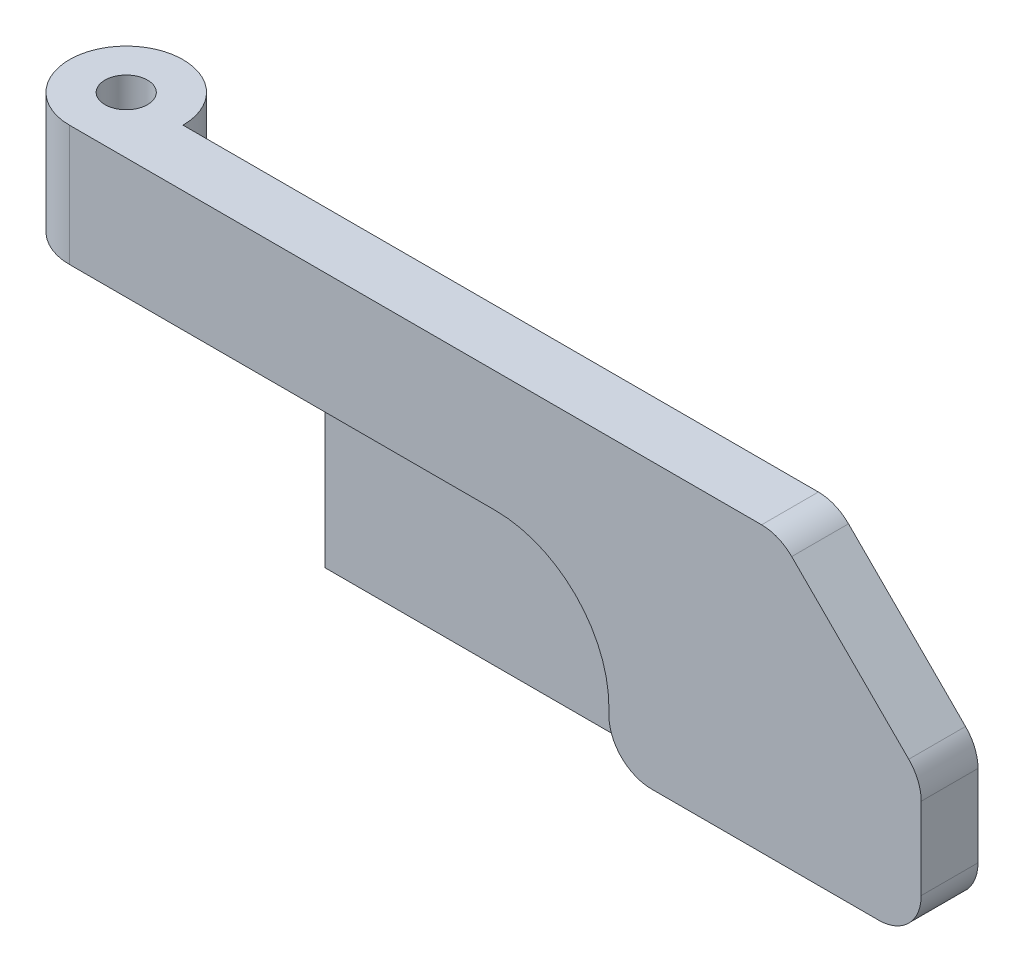
SolidWorks part; units mm, degrees
ref_plane "Alzado" through (0, 0, 0) normal (0, 0, 1) x (1, 0, 0)
ref_plane "Planta" through (0, 0, 0) normal (0, 1, 0) x (1, 0, 0)
ref_plane "Vista lateral" through (0, 0, 0) normal (1, 0, 0) x (0, 0, -1)
sketch "Croquis1" plane through (0, 0, 0) normal (0, 1, 0) x (1, 0, 0)
  line L0 (4, 0) -> (60, 0)
  line L1 (0, -4) -> (60, -4)
  line L2 (60, -4) -> (60, 0)
  circle A0 centre (0, 0) radius 1.5
  circle A1 centre (0, 0) radius 4
  dimension "D1" = 3
  dimension "D2" = 8
  dimension "D3" = 60
extrude "Saliente-Extruir1" add sketch "Croquis1" along normal blind 20 contours A1 A0 | A1 L1 L2 L0
sketch "Croquis2" plane through (0, 0, 4) normal (0, 0, 1) x (1, 0, 0)
  line L0 (16, 11.5) -> (16, 0)
  line L1 (0, 0) -> (60, 0) construction
  line L2 (16, 0) -> (-11.8072, 0)
  line L3 (-11.8072, 0) -> (-11.8072, 11.5)
  line L4 (-11.8072, 11.5) -> (16, 11.5)
  line L5 (-4, 20) -> (-4, 0) construction
  dimension "D1" = 11.5
  dimension "D2" = 20
extrude "Cortar-Extruir1" cut sketch "Croquis2" against normal blind 20
sketch "Croquis3" plane through (0, 0, 4) normal (0, 0, 1) x (1, 0, 0)
  line L0 (16, 0) -> (16, 11.5)
  line L1 (16, 11.5) -> (38, 11.5)
  line L2 (38, 11.5) -> (38, 0)
  line L3 (16, 0) -> (60, 0) construction
  line L4 (38, 0) -> (16, 0)
  dimension "D1" = 22
extrude "Cortar-Extruir2" cut sketch "Croquis3" against normal blind 2
chamfer "Chaflán1" distance 10 angle 45 1 edges at (60, 20, 2)
fillet "Redondeo1" radius 3 1 edges at (60, 0, 2)
fillet "Redondeo2" radius 3 2 edges at (50, 20, 2) (60, 10, 2)
fillet "Redondeo3" radius 3 1 edges at (38, 0, 3)
fillet "Redondeo4" radius 8 1 edges at (38, 11.5, 3)
